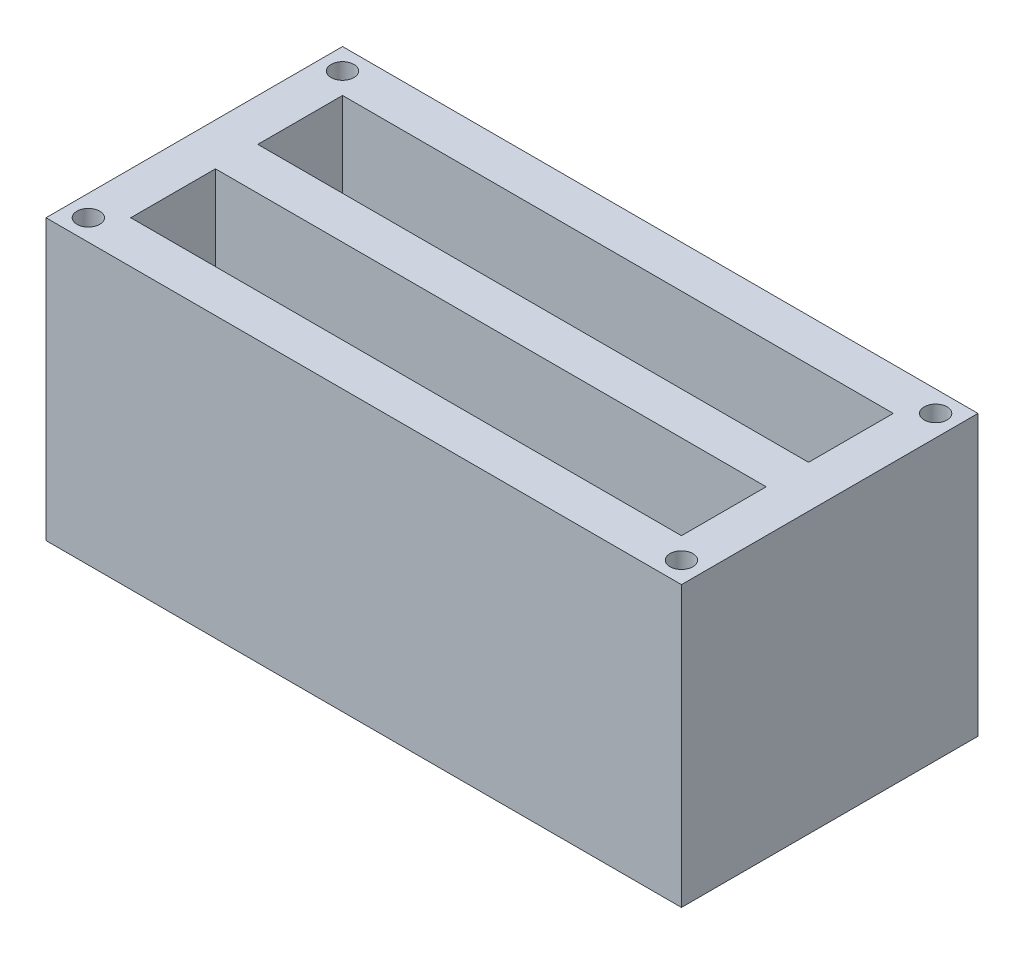
SolidWorks part; units mm, degrees
material "ABS"
ref_plane "Front Plane" through (0, 0, 0) normal (0, 0, 1) x (1, 0, 0)
ref_plane "Top Plane" through (0, 0, 0) normal (0, 1, 0) x (1, 0, 0)
ref_plane "Right Plane" through (0, 0, 0) normal (1, 0, 0) x (0, 0, -1)
sketch "Sketch1" plane through (0, 0, 0) normal (0, 1, 0) x (1, 0, 0)
  line L1 (0, 0) -> (75, 0)
  line L2 (0, 0) -> (0, 35)
  line L3 (0, 35) -> (75, 35)
  line L4 (75, 0) -> (75, 35)
  dimension "D1" = 35
  dimension "D2" = 75
extrude "Boss-Extrude1" add sketch "Sketch1" along normal blind 3
sketch "Sketch2" plane through (0, 3, 0) normal (0, 1, 0) x (1, 0, 0)
  line L0 (5, 30) -> (5, 20)
  line L1 (5, 5) -> (70, 5)
  line L2 (70, 5) -> (70, 15)
  line L3 (70, 30) -> (5, 30)
  line L4 (5, 20) -> (70, 20)
  line L5 (5, 15) -> (70, 15)
  line L7 (5, 15) -> (5, 5)
  line L8 (0, 35) -> (0, 0)
  line L9 (0, 0) -> (75, 0)
  line L10 (75, 0) -> (75, 35)
  line L11 (75, 35) -> (0, 35)
  line L12 (0, 35) -> (0, 0)
  line L13 (0, 0) -> (75, 0)
  line L14 (75, 0) -> (75, 35)
  line L15 (75, 35) -> (0, 35)
  line L16 (5, 30) -> (5, 5) construction
  line L17 (70, 20) -> (70, 30)
  line L18 (70, 5) -> (70, 30) construction
  point P12 (75, 17.5)
  dimension "D3" = 5
  dimension "D4" = 2.5
  dimension "D1" = 0
  dimension "D2" = 5
extrude "Boss-Extrude2" add sketch "Sketch2" along normal blind 30
sketch "Sketch3" plane through (0, 0, 0) normal (0, -1, 0) x (1, 0, 0)
  line L0 (0, -17.5) -> (75, -17.5) construction
  line L1 (0, -35) -> (0, 0) construction
  line L2 (75, 0) -> (75, -35) construction
  line L3 (0, -29) -> (75, -29) construction
  line L4 (0, -14) -> (75, -14) construction
  text T0 "FOLLOW ME" font "Century Gothic" height 8
  text T1 "STOP" font "Century Gothic" height 8
  point P6 (0, 0)
  point P7 (0, -17.5)
  dimension "D1" = 11.5
  dimension "D2" = 3.5
extrude "Cut-Extrude1" cut sketch "Sketch3" against normal through all
sketch "Sketch4" plane through (0, 33, 0) normal (0, 1, 0) x (1, 0, 0)
  line L4 (0, 35) -> (0, 0) construction
  line L5 (75, 35) -> (0, 35) construction
  line L6 (0, 0) -> (75, 0) construction
  line L7 (75, 0) -> (75, 35) construction
  circle A0 centre (2.5, 32.5) radius 1.35
  circle A1 centre (2.5, 2.5) radius 1.35
  circle A2 centre (72.5, 2.5) radius 1.35
  circle A3 centre (72.5, 32.5) radius 1.35
  point P8 (27.4225, 13.1383)
  point P9 (27.4225, 13.1383)
  point P10 (27.4225, 13.1383)
  point P11 (27.4225, 13.1383)
  dimension "D1" = 2.7
  dimension "D3" = 2.5
  dimension "D4" = 2.5
  dimension "D5" = 2.5
  dimension "D2" = 2.5
extrude "Cut-Extrude2" cut sketch "Sketch4" against normal blind 15
sketch "Sketch5" plane through (0, 0, -35) normal (0, 0, -1) x (-1, 0, 0)
  line L0 (-75, 33) -> (-75, 0) construction
  line L1 (0, 33) -> (0, 0) construction
  line L2 (-75, 33) -> (0, 33) construction
  circle A0 centre (-55, 18) radius 1.35
  circle A1 centre (-20, 18) radius 1.35
  point P10 (0, 0)
  dimension "D1" = 2.7
  dimension "D3" = 2.7
  dimension "D5" = 15
  dimension "D2" = 20
  dimension "D4" = 20
extrude "Cut-Extrude3" cut sketch "Sketch5" against normal up to surface (15 mm away) up to face at (37.5, 18, -20)
